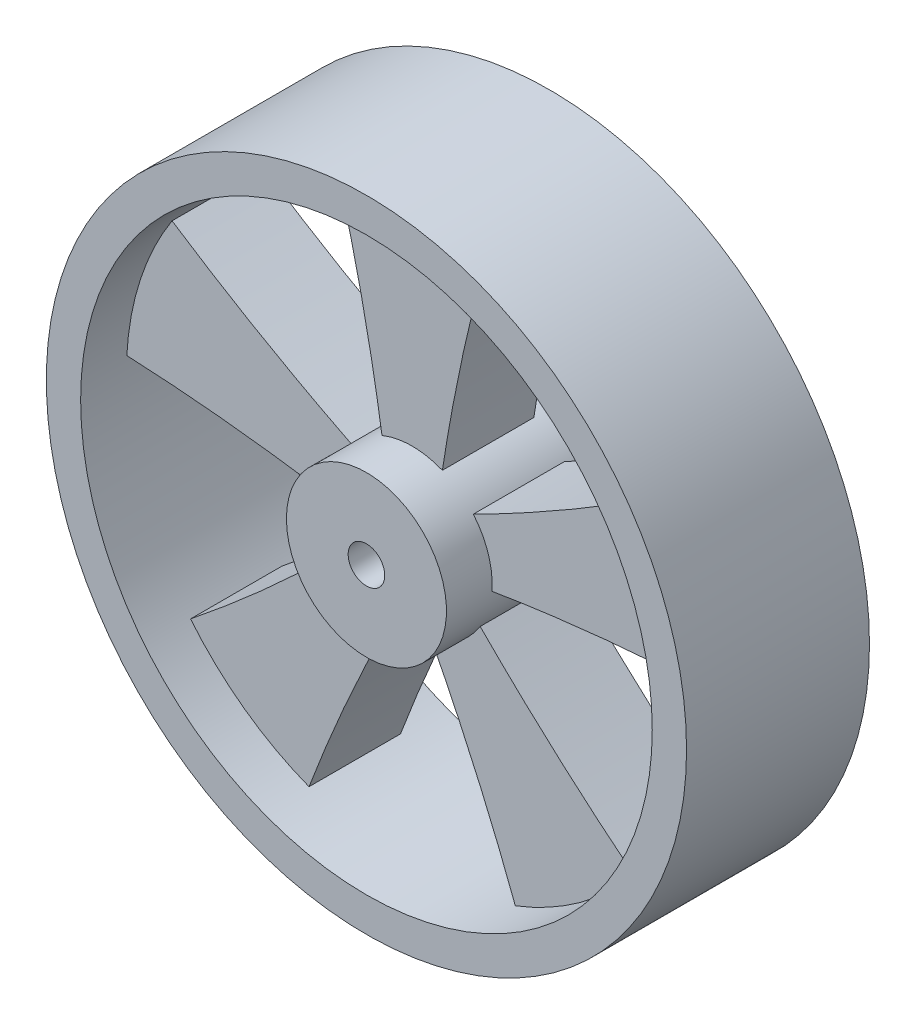
SolidWorks part; units mm, degrees
material "1060-H12"
ref_plane "Front Plane" through (0, 0, 0) normal (0, 0, 1) x (1, 0, 0)
ref_plane "Top Plane" through (0, 0, 0) normal (0, 1, 0) x (1, 0, 0)
ref_plane "Right Plane" through (0, 0, 0) normal (1, 0, 0) x (0, 0, -1)
sketch "Sketch1" plane through (0, 0, 0) normal (0, 0, 1) x (1, 0, 0)
  circle A0 centre (0, 0) radius 62.2786
  circle A1 centre (0, 0) radius 70
  circle A2 centre (0, 0) radius 17.1215
  circle A3 centre (0, 0) radius 4
  dimension "D1" = 140
  dimension "D2" = 8
extrude "Boss-Extrude1" add sketch "Sketch1" along normal mid plane 40 contours A1 A0 | A0 A2 | A2 A3
sketch "Sketch2" plane through (0, 0, -20) normal (0, 0, -1) x (-1, 0, 0)
  circle A0 centre (0, 0) radius 17.5
  circle A1 centre (0, 0) radius 62.5
  dimension "D1" = 125
  dimension "D2" = 35
extrude "Cut-Extrude1" cut sketch "Sketch2" against normal blind 10
mirror "Mirror1" about plane through (0, 0, 0) normal (0, 0, 1) of "Cut-Extrude1"
sketch "Sketch3" plane through (0, 0, -10) normal (0, 0, -1) x (-1, 0, 0)
  line L0 (0, 0) -> (0, 62.5) construction
  circle A0 centre (0, 0) radius 62.5 construction
  circle A1 centre (0, 0) radius 62.5 construction
  circle A2 centre (0, 0) radius 17.5 construction
  circle A4 centre (0, 0) radius 62.5
  circle A5 centre (0, 0) radius 17.5
  spline S0 degree 2 poles (-16.0122, 60.4141) (-10.0282, 38.5892) (-6.6036, 16.2063) knots 0 0 0 1 1 1
  spline S1 degree 2 poles (16.0122, 60.4141) (10.0282, 38.5892) (6.6036, 16.2063) knots 0 0 0 1 1 1
  spline S2 degree 2 poles (62.4052, 3.4405) (39.7994, 2.3873) (17.4537, -1.2724) knots 0 0 0 1 1 1
  spline S3 degree 2 poles (52.5092, 33.8975) (33.6017, 21.4621) (13.3725, 11.2884) knots 0 0 0 1 1 1
  spline S4 degree 2 poles (22.5564, -58.2877) (14.5692, -37.1138) (4.1834, -16.9926) knots 0 0 0 1 1 1
  spline S5 degree 2 poles (48.4646, -39.4643) (30.7952, -25.3249) (14.8682, -9.2297) knots 0 0 0 1 1 1
  spline S6 degree 2 poles (-48.4646, -39.4643) (-30.7952, -25.3249) (-14.8682, -9.2297) knots 0 0 0 1 1 1
  spline S7 degree 2 poles (-22.5564, -58.2877) (-14.5692, -37.1138) (-4.1834, -16.9926) knots 0 0 0 1 1 1
  spline S8 degree 2 poles (-52.5092, 33.8975) (-33.6017, 21.4621) (-13.3725, 11.2884) knots 0 0 0 1 1 1
  spline S9 degree 2 poles (-62.4052, 3.4405) (-39.7994, 2.3873) (-17.4537, -1.2724) knots 0 0 0 1 1 1
  point P43 (0, 0)
  point P44 (0, 0)
  circle M2 centre (0, 0) radius 17.5
  circle M3 centre (0, 0) radius 62.5
extrude "Cut-Extrude2" cut sketch "Sketch3" against normal through all contours S8 A5 S0 M3 | S3 S1 A5 M3 | S5 S2 M3 M2 | S9 S6 M3 M2 | S7 S4 A5 M3
